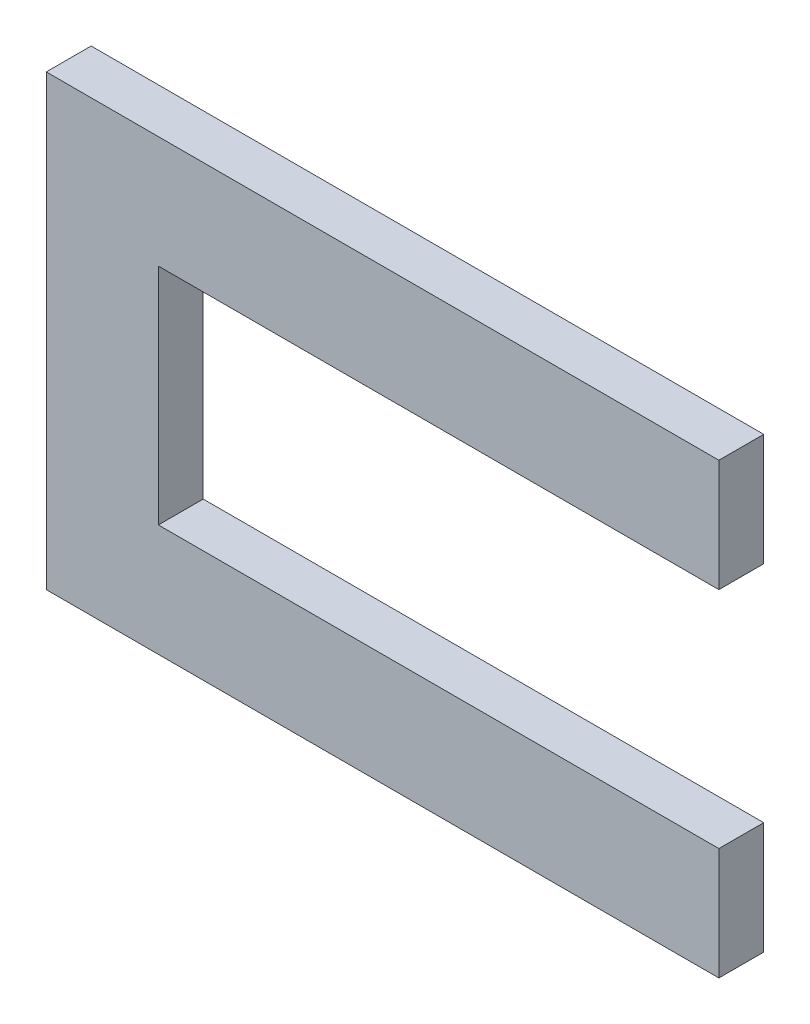
SolidWorks part; units mm, degrees
ref_plane "Front Plane" through (0, 0, 0) normal (0, 0, 1) x (1, 0, 0)
ref_plane "Top Plane" through (0, 0, 0) normal (0, 1, 0) x (1, 0, 0)
ref_plane "Right Plane" through (0, 0, 0) normal (1, 0, 0) x (0, 0, -1)
sketch "Sketch1" plane through (0, 0, 0) normal (0, 0, 1) x (1, 0, 0)
  line L0 (-15, -10) -> (15, 10) construction
  line L1 (-15, 10) -> (15, 10)
  line L2 (-15, 10) -> (-15, -10)
  line L3 (-15, -10) -> (15, -10)
  line L4 (15, 10) -> (15, -10)
  line L5 (-10, 5) -> (15, 5)
  line L6 (15, 5) -> (15, -5)
  line L7 (15, -5) -> (-10, -5)
  line L8 (-10, -5) -> (-10, 5)
  line L9 (-10, 0) -> (-15, 0)
  dimension "D1" = 10
  dimension "D2" = 25
  dimension "D3" = 30
  dimension "D4" = 20
extrude "Boss-Extrude1" add sketch "Sketch1" along normal blind 2 contours L5 L0 L1 L2 L9 L8 | L0 L3 L4 L7 | L0 L5 L4 | L2 L0 L7 L8 L9
